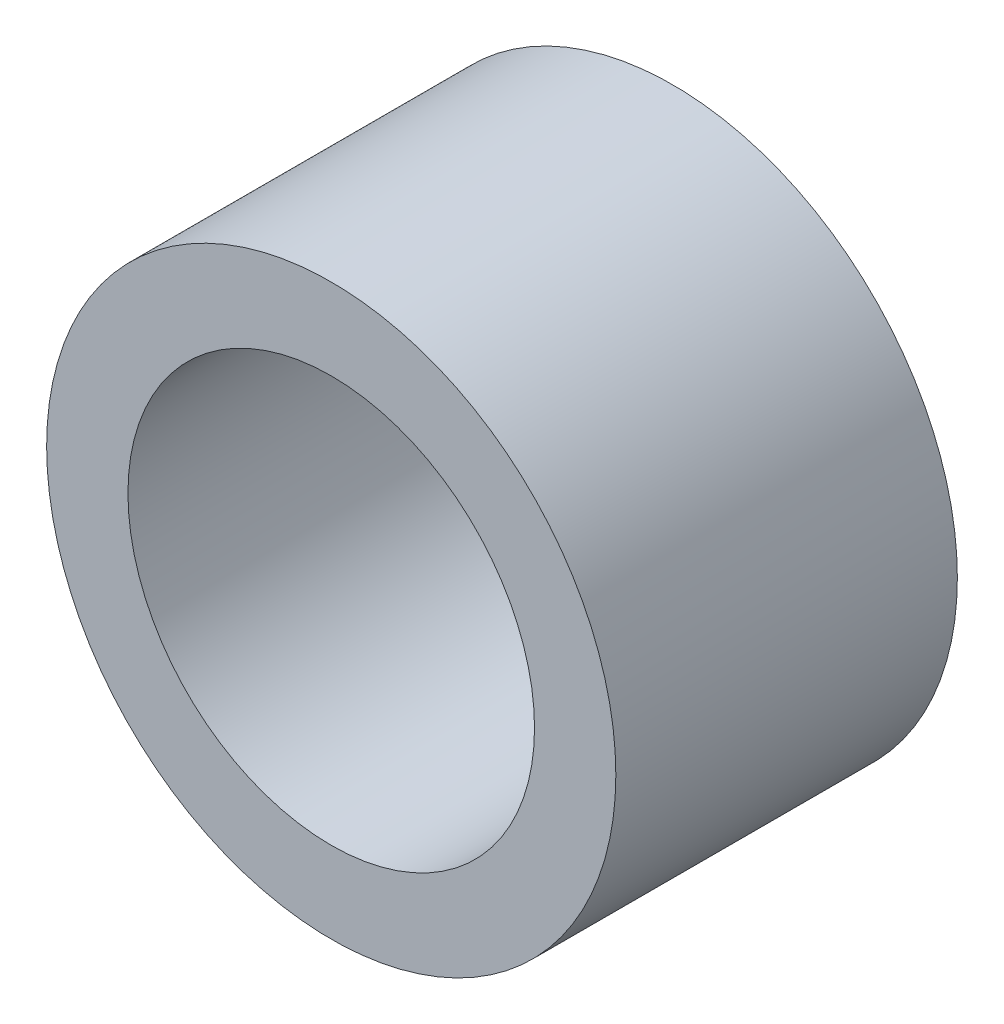
SolidWorks part; units mm, degrees
ref_plane "Front Plane" through (0, 0, 0) normal (0, 0, 1) x (1, 0, 0)
ref_plane "Top Plane" through (0, 0, 0) normal (0, 1, 0) x (1, 0, 0)
ref_plane "Right Plane" through (0, 0, 0) normal (1, 0, 0) x (0, 0, -1)
sketch "Sketch1" plane through (0, 0, 0) normal (0, 0, 1) x (1, 0, 0)
  circle A0 centre (0, 0) radius 17.5
  circle A1 centre (0, 0) radius 12.5
extrude "Output_Stopper_Tube_35x25x21" add sketch "Sketch1" along normal blind 21
